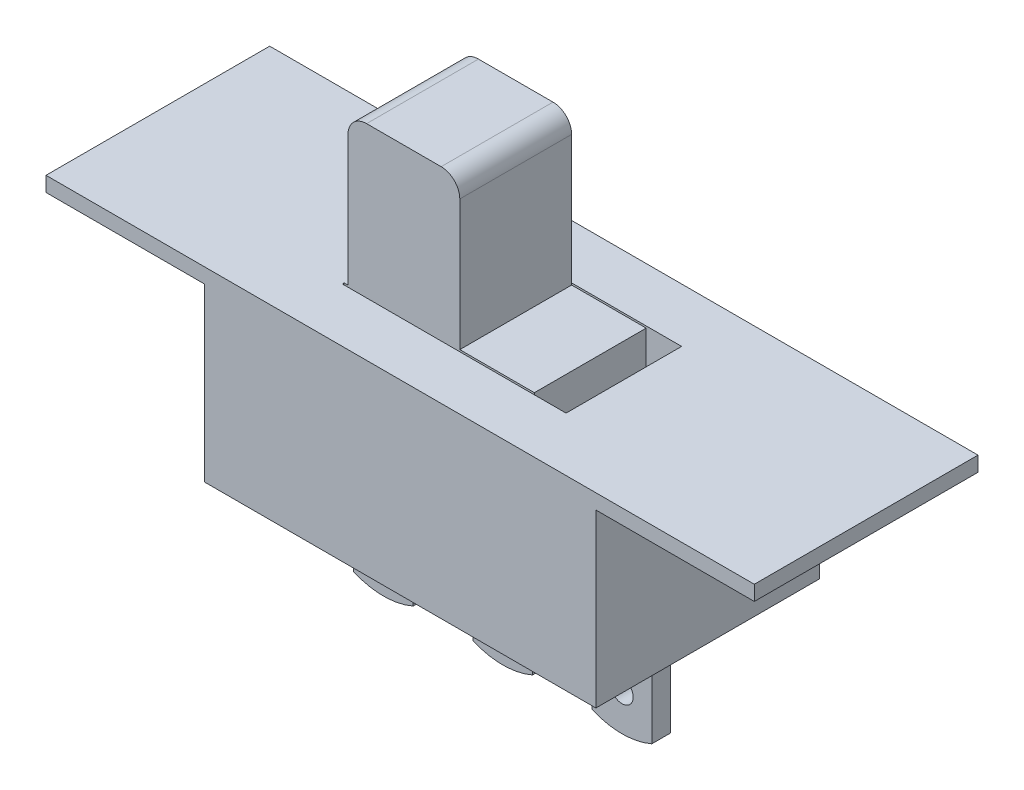
SolidWorks part; units mm, degrees
ref_plane "Front Plane" through (0, 0, 0) normal (0, 0, 1) x (1, 0, 0)
ref_plane "Top Plane" through (0, 0, 0) normal (0, 1, 0) x (1, 0, 0)
ref_plane "Right Plane" through (0, 0, 0) normal (1, 0, 0) x (0, 0, -1)
sketch "Sketch1" plane through (0, 0, 0) normal (0, 0, 1) x (1, 0, 0)
  line L1 (-5.25, 0) -> (5.25, 0)
  line L2 (-5.25, 0) -> (-5.25, 5)
  line L3 (-5.25, 5) -> (5.25, 5)
  line L4 (5.25, 0) -> (5.25, 5)
  dimension "D1" = 10.5
  dimension "D2" = 5
extrude "BASE" add sketch "Sketch1" along normal mid plane 6
sketch "Sketch2" plane through (0, 5, 0) normal (0, 1, 0) x (1, 0, 0)
  line L0 (5.25, -3) -> (-5.25, -3) construction
  line L2 (9.5, -3) -> (-9.5, -3)
  line L3 (9.5, -3) -> (9.5, 3)
  line L6 (9.5, 3) -> (-9.5, 3)
  line L7 (-9.5, -3) -> (-9.5, 3)
  line L8 (9.5, -3) -> (-9.5, 3) construction
  line L9 (9.5, 3) -> (-9.5, -3) construction
  point P0 (0, 0)
  dimension "D1" = 19
extrude "FLANGE" add sketch "Sketch2" against normal blind 0.4
sketch "Sketch3" plane through (0, 5, 0) normal (0, 1, 0) x (1, 0, 0)
  line L0 (0, 3) -> (0, -3) construction
  line L1 (9.5, 3) -> (-9.5, 3) construction
  line L2 (9.5, -3) -> (-9.5, -3) construction
  line L3 (0, 0) -> (23.8748, 0) construction
  line L5 (-3, 1.55) -> (3, 1.55)
  line L6 (-3, 1.55) -> (-3, -1.55)
  line L7 (-3, -1.55) -> (3, -1.55)
  line L8 (3, 1.55) -> (3, -1.55)
  dimension "D1" = 3.1
  dimension "D2" = 6
extrude "SWITCH ENCOMPASSING CUT" cut sketch "Sketch3" against normal blind 1
sketch "Sketch4" plane through (0, 4, 0) normal (0, 1, 0) x (1, 0, 0)
  line L0 (-3, 0) -> (3, 0) construction
  line L1 (-2.9, 1.5) -> (0.1, 1.5)
  line L2 (-2.9, 1.5) -> (-2.9, -1.5)
  line L3 (-2.9, -1.5) -> (0.1, -1.5)
  line L4 (0.1, 1.5) -> (0.1, -1.5)
  line L5 (-3, 1.55) -> (-3, -1.55) construction
  line L6 (3, -1.55) -> (3, 1.55) construction
  dimension "D1" = 3
  dimension "D2" = 3
  dimension "D3" = 0.1
extrude "SWITCH" add sketch "Sketch4" along normal blind 5
sketch "Sketch7" plane through (0, 5, 0) normal (0, 1, 0) x (1, 0, 0)
  line L0 (-1.4, 1.5) -> (-1.4, -1.5) construction
  line L1 (-4.9, 1.5) -> (2.1, 1.5)
  line L2 (-4.9, 1.5) -> (-4.9, -1.5)
  line L3 (-4.9, -1.5) -> (2.1, -1.5)
  line L4 (2.1, 1.5) -> (2.1, -1.5)
  line L5 (0.1, 1.5) -> (-2.9, 1.5) construction
  line L6 (-2.9, -1.5) -> (0.1, -1.5) construction
  dimension "D1" = 7
extrude "SWITCH BASE" add sketch "Sketch7" against normal up to surface (1 mm away) up to face at (0, 4, 0)
sketch "Sketch6" plane through (0, 0, 0) normal (0, 0, 1) x (1, 0, 0)
  line L0 (0, 0) -> (0, -3) construction
  line L1 (-5.25, 0) -> (5.25, 0) construction
  line L3 (-0.8, 0) -> (0.8, 0)
  line L4 (-0.8, 0) -> (-0.8, -2.833)
  line L6 (0.8, 0) -> (0.8, -2.833)
  arc A0 (-0.8, -2.833) -> (0.8, -2.833) centre (0, -1) ccw
  circle A1 centre (0, -2) radius 0.3
  dimension "D4" = 0.6
  dimension "D1" = 1.6
  dimension "D2" = 3
  dimension "D3" = 2
  dimension "D5" = 1
extrude "LEG" add sketch "Sketch6" against normal mid plane 0.5
pattern_linear "L LEFT" count 2 spacing 3.2 along (1, 0, 0) of "LEG"
pattern_linear "L RIGHT" count 2 spacing 3.2 along (-1, 0, 0) of "LEG"
fillet "S F" radius 0.5 2 edges at (0.1, 9, 0) (-2.9, 9, 0)
